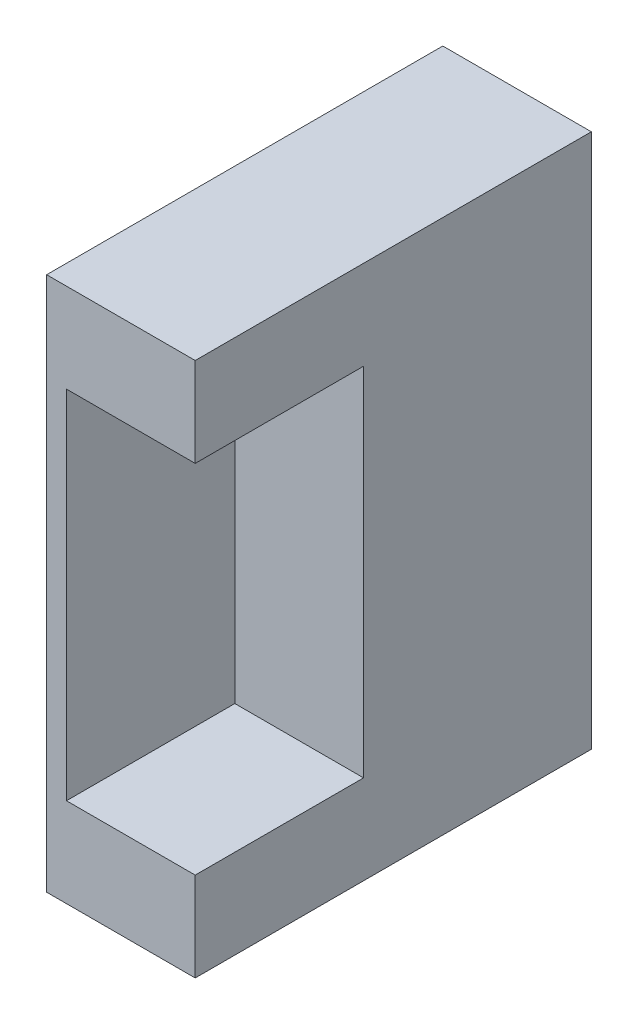
SolidWorks part; units mm, degrees
ref_plane "Front Plane" through (0, 0, 0) normal (1, 0, 0) x (0, 1, 0)
ref_plane "Top Plane" through (0, 0, 0) normal (0, 0, 1) x (0, 1, 0)
ref_plane "Right Plane" through (0, 0, 0) normal (0, 1, 0) x (-1, 0, 0)
sketch "Sketch1" plane through (0, 0, 0) normal (1, 0, 0) x (0, 1, 0)
  line L1 (0, 0) -> (68.58, 0)
  line L2 (0, 0) -> (0, 50.8)
  line L3 (0, 50.8) -> (68.58, 50.8)
  line L4 (68.58, 0) -> (68.58, 50.8)
  dimension "D1" = 68.58
  dimension "D2" = 50.8
extrude "Boss-Extrude1" add sketch "Sketch1" along normal blind 19.05
sketch "Sketch2" plane through (19.05, 0, 0) normal (1, 0, 0) x (0, 1, 0)
  line L0 (68.58, 50.8) -> (0, 50.8) construction
  line L1 (11.43, 50.8) -> (57.15, 50.8)
  line L2 (11.43, 50.8) -> (11.43, 29.21)
  line L3 (11.43, 29.21) -> (57.15, 29.21)
  line L4 (57.15, 50.8) -> (57.15, 29.21)
  line L5 (0, 50.8) -> (0, 0) construction
  dimension "D1" = 45.72
  dimension "D2" = 21.59
  dimension "D3" = 11.43
extrude "Cut-Extrude1" cut sketch "Sketch2" against normal blind 16.51
